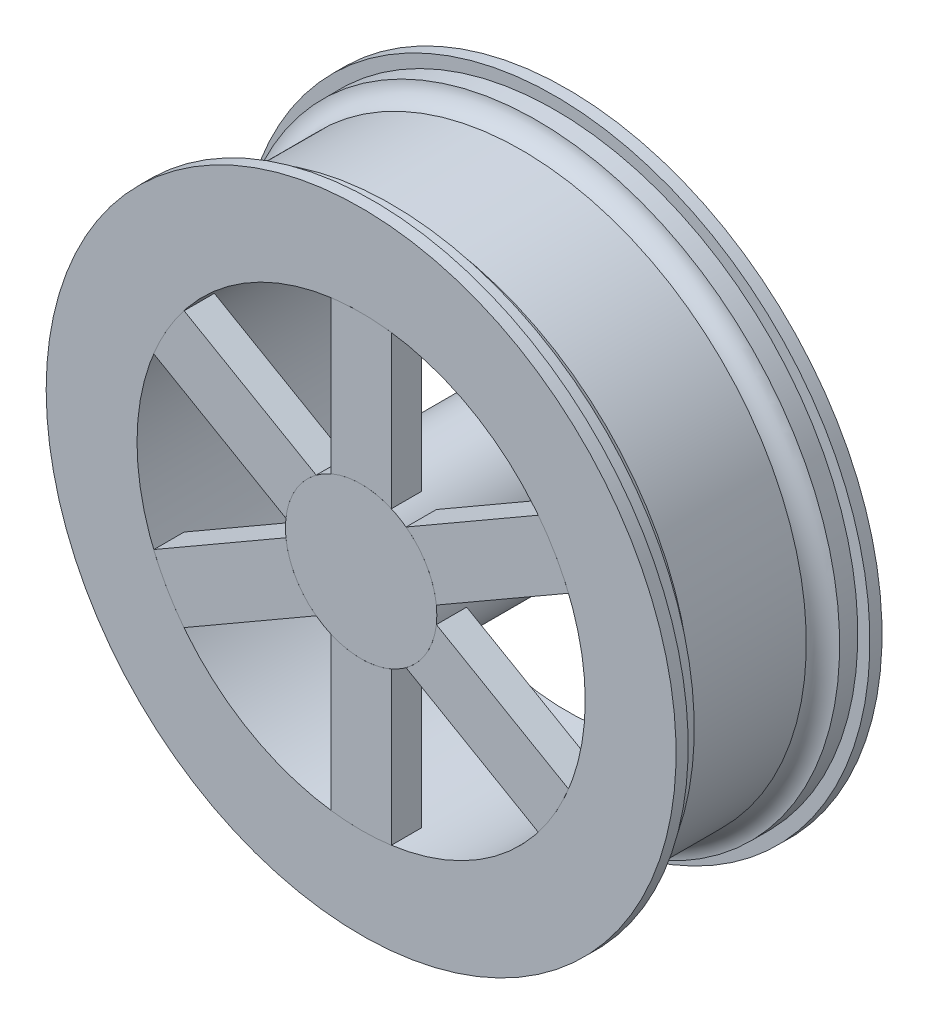
SolidWorks part; units mm, degrees
ref_plane "Front Plane" through (0, 0, 0) normal (0, 0, 1) x (1, 0, 0)
ref_plane "Top Plane" through (0, 0, 0) normal (0, 1, 0) x (1, 0, 0)
ref_plane "Right Plane" through (0, 0, 0) normal (1, 0, 0) x (0, 0, -1)
sketch "Sketch1" plane through (0, 0, 0) normal (1, 0, 0) x (0, 0, -1)
  line L0 (0, 0) -> (24.5759, 0) construction
  line L1 (2, 50) -> (2, 52)
  line L2 (2, 50) -> (5, 50)
  line L3 (2, 52) -> (0, 52)
  line L4 (17, 0) -> (17, 61.2694) construction
  line L5 (7.5, 47) -> (26.5, 47)
  line L6 (0, 52) -> (0, 37)
  line L7 (0, 37) -> (34, 37)
  line L8 (17, 37) -> (17, 47)
  line L9 (34, 52) -> (34, 37)
  line L10 (32, 52) -> (34, 52)
  line L11 (32, 50) -> (32, 52)
  line L12 (32, 50) -> (29, 50)
  arc A0 (5, 50) -> (7.5, 47) centre (8.4815, 50.3596) ccw
  arc A1 (29, 50) -> (26.5, 47) centre (25.5185, 50.3596) cw
  dimension "D6" = 3.5
  dimension "D1" = 50
  dimension "D2" = 37
  dimension "D3" = 3
  dimension "D4" = 15
  dimension "D5" = 3
  dimension "D7" = 9.5
  dimension "D8" = 17
  dimension "D9" = 2
revolve "Revolve1" add sketch "Sketch1" angle 360 about L0
sketch "Sketch2" plane through (0, 0, 0) normal (0, 0, 1) x (1, 0, 0)
  circle A0 centre (0, 0) radius 12.5
  circle A1 centre (0, 0) radius 7.5
  dimension "D1" = 25
  dimension "D2" = 15
extrude "Boss-Extrude1" add sketch "Sketch2" against normal blind 45 separate body contours A1 | A0 A1
sketch "Sketch3" plane through (0, 0, 0) normal (0, 0, 1) x (1, 0, 0)
  line L0 (0, 52) -> (0, -52) construction
  line L1 (-5, 11.4564) -> (-5, 36.6606)
  line L2 (5, 11.4564) -> (5, 36.6606)
  line L17 (12.4216, 1.3981) -> (34.249, 14.0002)
  line L18 (7.4216, 10.0583) -> (29.249, 22.6604)
  line L19 (7.4216, -10.0583) -> (29.249, -22.6604)
  line L20 (12.4216, -1.3981) -> (34.249, -14.0002)
  line L21 (-5, -11.4564) -> (-5, -36.6606)
  line L22 (5, -11.4564) -> (5, -36.6606)
  line L23 (-12.4216, -1.3981) -> (-34.249, -14.0002)
  line L24 (-7.4216, -10.0583) -> (-29.249, -22.6604)
  line L25 (-7.4216, 10.0583) -> (-29.249, 22.6604)
  line L26 (-12.4216, 1.3981) -> (-34.249, 14.0002)
  circle A0 centre (0, 0) radius 52 construction
  circle A1 centre (0, 0) radius 12.5 construction
  circle A2 centre (0, 0) radius 37 construction
  arc A3 (-5, 11.4564) -> (5, 11.4564) centre (0, 0) cw
  arc A4 (-5, 36.6606) -> (5, 36.6606) centre (0, 0) cw
  arc A19 (7.4216, 10.0583) -> (12.4216, 1.3981) centre (0, 0) cw
  arc A20 (29.249, 22.6604) -> (34.249, 14.0002) centre (0, 0) cw
  arc A21 (12.4216, -1.3981) -> (7.4216, -10.0583) centre (0, 0) cw
  arc A22 (34.249, -14.0002) -> (29.249, -22.6604) centre (0, 0) cw
  arc A23 (5, -11.4564) -> (-5, -11.4564) centre (0, 0) cw
  arc A24 (5, -36.6606) -> (-5, -36.6606) centre (0, 0) cw
  arc A25 (-7.4216, -10.0583) -> (-12.4216, -1.3981) centre (0, 0) cw
  arc A26 (-29.249, -22.6604) -> (-34.249, -14.0002) centre (0, 0) cw
  arc A27 (-12.4216, 1.3981) -> (-7.4216, 10.0583) centre (0, 0) cw
  arc A28 (-34.249, 14.0002) -> (-29.249, 22.6604) centre (0, 0) cw
  point P38 (0, 0)
  point P45 (0, 0)
  dimension "D2" = 6
  dimension "D3" = 37
  dimension "D1" = 5
extrude "Boss-Extrude6" add sketch "Sketch3" against normal blind 5 separate body contours A26 L23 A25 L24
sketch "Sketch4" plane through (0, 0, -45) normal (0, 0, -1) x (-1, 0, 0)
  line L0 (0, 12.5) -> (0, -12.5) construction
  line L1 (-12.5, 0) -> (12.5, 0) construction
  line L2 (-1.52, 0) -> (1.52, 0) construction
  line L3 (-1.52, 1.97) -> (1.52, 1.97)
  line L4 (-1.52, -1.97) -> (1.52, -1.97)
  circle A3 centre (0, 0) radius 12.5 construction
  arc A4 (-1.52, 1.97) -> (-1.52, -1.97) centre (-1.52, 0) ccw
  arc A5 (1.52, -1.97) -> (1.52, 1.97) centre (1.52, 0) ccw
  arc A6 (12.4216, 1.3981) -> (7.4216, 10.0583) centre (0, 0) ccw construction
  point P2 (0, 0)
  point P3 (0, 0)
  point P4 (0, 0)
  point P5 (0, 0)
  point P11 (0, 0)
  point P18 (0, 0)
  dimension "D1" = 1.52
  dimension "D2" = 3.94
extrude "Cut-Extrude1" cut sketch "Sketch4" against normal up to surface (40 mm away) up to face at (0, 24.4043, -5)
